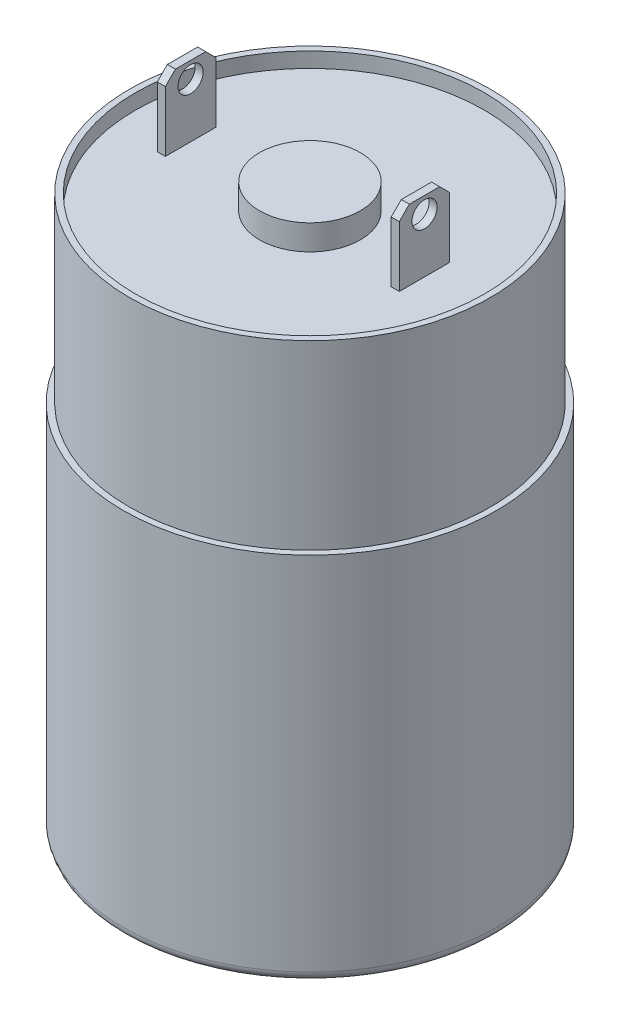
SolidWorks part; units mm, degrees
material "3.0205 (EN-AW 1200)"
ref_plane "Alzado" through (0, 0, 0) normal (0, 0, 1) x (1, 0, 0)
ref_plane "Planta" through (0, 0, 0) normal (0, 1, 0) x (1, 0, 0)
ref_plane "Vista lateral" through (0, 0, 0) normal (1, 0, 0) x (0, 0, -1)
sketch "Croquis1" plane through (0, 0, 0) normal (0, 1, 0) x (1, 0, 0)
  circle A0 centre (0, 0) radius 18.5
  dimension "D1" = 37
extrude "Saliente-Extruir1" add sketch "Croquis1" along normal mid plane 36.8
sketch "Croquis2" plane through (0, 18.4, 0) normal (0, 1, 0) x (1, 0, 0)
  circle A0 centre (0, 0) radius 17.9
  dimension "D1" = 35.8
extrude "Saliente-Extruir2" add sketch "Croquis2" along normal blind 18
sketch "Croquis3" plane through (0, 36.4, 0) normal (0, 1, 0) x (1, 0, 0)
  circle A0 centre (0, 0) radius 17.3
  dimension "D1" = 34.6
extrude "Cortar-Extruir1" cut sketch "Croquis3" against normal blind 1.5
sketch "Croquis4" plane through (0, 34.9, 0) normal (0, 1, 0) x (1, 0, 0)
  circle A0 centre (0, 0) radius 5
  dimension "D1" = 10
extrude "Saliente-Extruir3" add sketch "Croquis4" along normal blind 2.5
sketch "Croquis5" plane through (0, 34.9, 0) normal (0, 1, 0) x (1, 0, 0)
  line L0 (-11.8389, -2.5) -> (-11.8389, 2.5)
  line L2 (-11.8389, -2.5) -> (-12.6389, -2.5)
  line L3 (-11.8389, -2.5) -> (-11.8389, 2.5)
  line L4 (-11.8389, 2.5) -> (-12.6389, 2.5)
  line L5 (-12.6389, -2.5) -> (-12.6389, 2.5)
  point P2 (-11.8389, 0)
  dimension "D1" = 12.1
  dimension "D2" = 5
  dimension "D3" = 0.8
extrude "Saliente-Extruir4" add sketch "Croquis5" along normal blind 7 contours L5 L2 L0 L4
chamfer "Chaflán1" distance 1 angle 45 1 edges at (-12.2389, 41.9, 2.5)
chamfer "Chaflán2" distance 1 angle 45 1 edges at (-12.2389, 41.9, -2.5)
sketch "Croquis6" plane through (-11.8389, 0, 0) normal (1, 0, 0) x (0, 0, -1)
  line L0 (-1.5, 41.9) -> (1.5, 41.9) construction
  circle A0 centre (0, 40.2855) radius 1.25
  point P5 (0, 41.9)
  dimension "D1" = 2.5
extrude "Cortar-Extruir2" cut sketch "Croquis6" against normal blind 7
pattern_linear "MatrizL1" count 2 spacing 23.2 along (1, 0, 0) of "Cortar-Extruir2", "Chaflán2", "Saliente-Extruir4", "Chaflán1"
fillet "Redondeo1" radius 1 1 edges at (0, -18.4, 18.5)
